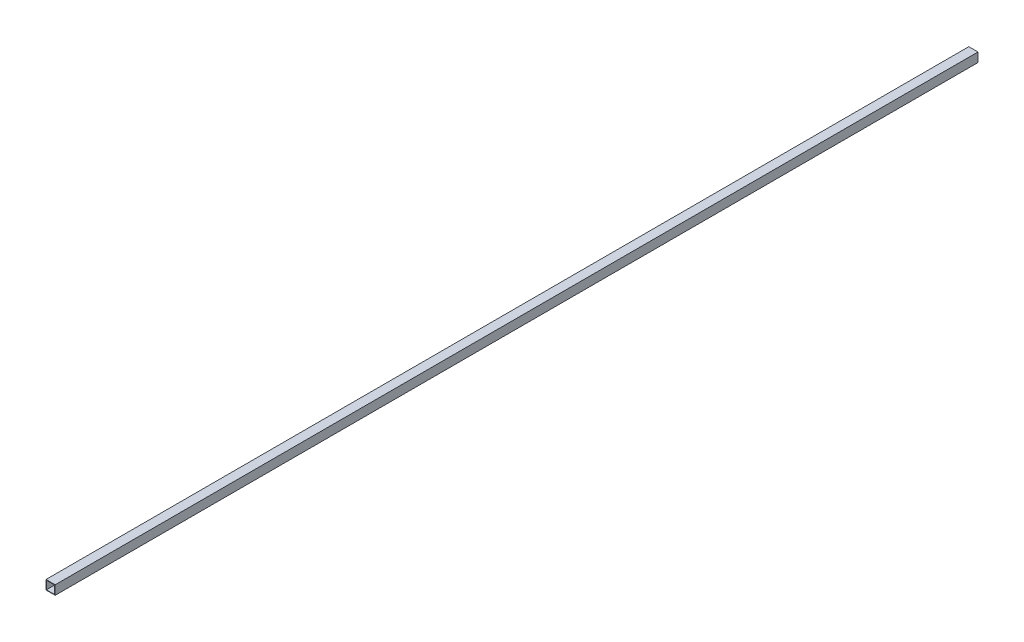
SolidWorks part; units mm, degrees
ref_plane "Alzado" through (0, 0, 0) normal (0, 0, 1) x (1, 0, 0)
ref_plane "Planta" through (0, 0, 0) normal (0, 1, 0) x (1, 0, 0)
ref_plane "Vista lateral" through (0, 0, 0) normal (1, 0, 0) x (0, 0, -1)
sketch "Croquis1" plane through (0, 0, 0) normal (0, 0, 1) x (1, 0, 0)
  line L1 (10, -10) -> (-10, -10)
  line L2 (10, -10) -> (10, 10)
  line L3 (10, 10) -> (-10, 10)
  line L4 (-10, -10) -> (-10, 10)
  line L5 (10, -10) -> (-10, 10) construction
  line L6 (10, 10) -> (-10, -10) construction
  circle A0 centre (0, 0) radius 14.1421 construction
  point P0 (0, 0)
  dimension "D1" = 20
extrude "Extruir-Lámina1" add sketch "Croquis1" along normal mid plane 2010 thin
